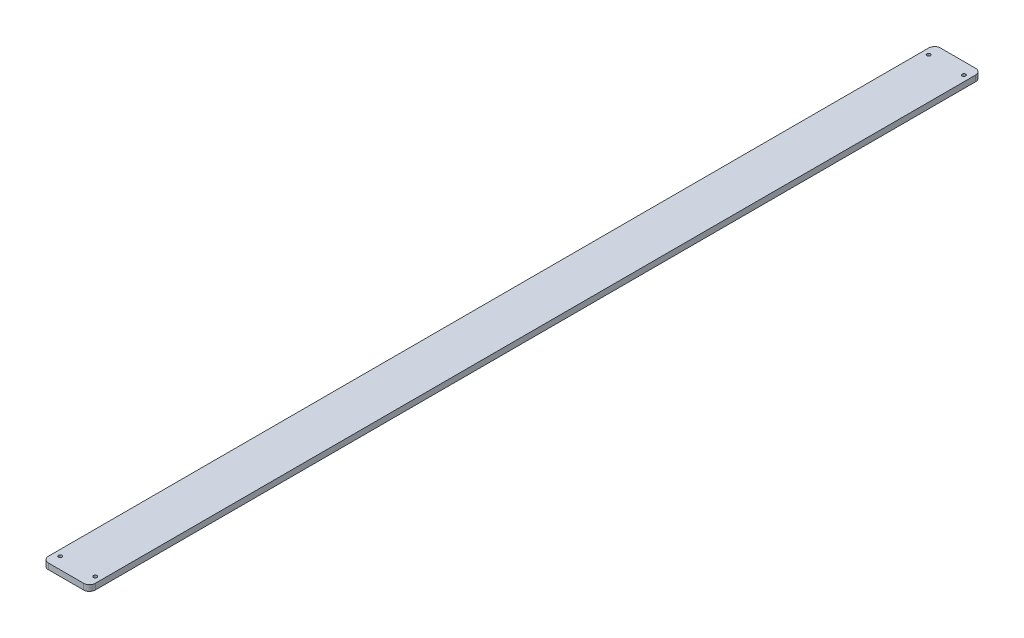
SolidWorks part; units mm, degrees
material "プラ段"
ref_plane "正面" through (0, 0, 0) normal (0, 0, 1) x (1, 0, 0)
ref_plane "平面" through (0, 0, 0) normal (0, 1, 0) x (1, 0, 0)
ref_plane "右側面" through (0, 0, 0) normal (1, 0, 0) x (0, 0, -1)
sketch "ｽｹｯﾁ1" plane through (0, 0, 0) normal (0, 1, 0) x (1, 0, 0)
  line L0 (0, 380.5) -> (0, -380.5) construction
  line L1 (-20, -380.5) -> (20, -380.5)
  line L2 (-20, -380.5) -> (-20, 380.5)
  line L3 (-20, 380.5) -> (20, 380.5)
  line L4 (20, -380.5) -> (20, 380.5)
  line L5 (-20, -380.5) -> (20, 380.5) construction
  line L6 (-20, 380.5) -> (20, -380.5) construction
  line L7 (-20, 0) -> (20, 0) construction
  circle A0 centre (15, 370.5) radius 1.5
  circle A1 centre (-15, 370.5) radius 1.5
  circle A2 centre (-15, -370.5) radius 1.5
  circle A3 centre (15, -370.5) radius 1.5
  point P0 (0, 0)
  dimension "D1" = 30
  dimension "D2" = 741
  dimension "D4" = 5
  dimension "D5" = 3
  dimension "D3" = 10
extrude "ﾎﾞｽ - 押し出し1" add sketch "ｽｹｯﾁ1" along normal blind 5
fillet "ﾌｨﾚｯﾄ1" radius 5 4 edges at (-20, 2.5, -380.5) (20, 2.5, -380.5) (-20, 2.5, 380.5) (20, 2.5, 380.5)
